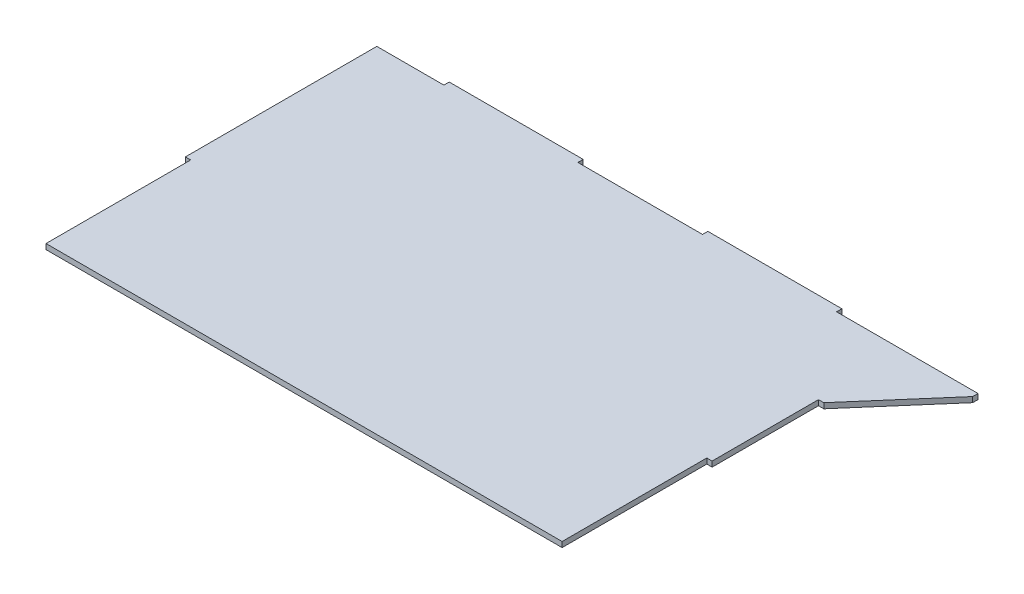
SolidWorks part; units mm, degrees
material "6061-T6 (SS)"
ref_plane "X-Y Datum" through (0, 0, 0) normal (0, 0, 1) x (1, 0, 0)
ref_plane "X-Z Datum" through (0, 0, 0) normal (0, 1, 0) x (1, 0, 0)
ref_plane "Y-Z Datum" through (0, 0, 0) normal (1, 0, 0) x (0, 0, -1)
sketch "Sketch1" plane through (0, 0, 0) normal (0, 0, 1) x (1, 0, 0)
  line L1 (-157.2306, -1.5875) -> (157.2306, -1.5875)
  line L2 (-157.2306, -1.5875) -> (-157.2306, 1.5875)
  line L3 (-157.2306, 1.5875) -> (157.2306, 1.5875)
  line L4 (157.2306, -1.5875) -> (157.2306, 1.5875)
  line L5 (-157.2306, -1.5875) -> (157.2306, 1.5875) construction
  line L6 (-157.2306, 1.5875) -> (157.2306, -1.5875) construction
  point P0 (0, 0)
  dimension "D1" = 314.4612
  dimension "D2" = 3.175
extrude "Boss-Extrude1" add sketch "Sketch1" along normal blind 200.6618
sketch "Sketch3" plane through (0, 0, 0) normal (0, 0, -1) x (-1, 0, 0)
  line L0 (-157.2306, 0) -> (-77.2306, 0) construction
  line L1 (-157.2306, -1.5875) -> (-157.2306, 1.5875) construction
  line L2 (-157.2306, 1.5875) -> (157.2306, 1.5875) construction
  line L3 (-117.2306, -1.5875) -> (-37.2306, -1.5875)
  line L4 (-117.2306, -1.5875) -> (-117.2306, 1.5875)
  line L5 (-117.2306, 1.5875) -> (-37.2306, 1.5875)
  line L6 (-37.2306, -1.5875) -> (-37.2306, 1.5875)
  line L7 (-117.2306, -1.5875) -> (-37.2306, 1.5875) construction
  line L8 (-117.2306, 1.5875) -> (-37.2306, -1.5875) construction
  line L14 (-157.2306, 1.5875) -> (-117.2306, 1.5875)
  line L15 (-157.2306, 1.5875) -> (-157.2306, -1.5875)
  line L16 (-157.2306, -1.5875) -> (-117.2306, -1.5875)
  line L17 (-117.2306, 1.5875) -> (-117.2306, -1.5875)
  line L19 (-37.2306, 1.5875) -> (-37.2306, -1.5875)
  line M3 (-157.2306, -1.5875) -> (157.2306, -1.5875)
  line M5 (157.2306, 1.5875) -> (-157.2306, 1.5875)
  dimension "D1" = 40
  dimension "D2" = 80
sketch "Sketch5" plane through (0, 1.5875, 0) normal (0, 1, 0) x (1, 0, 0)
  line L1 (-157.2306, -200.6618) -> (-154.0556, -200.6618)
  line L3 (-157.2306, -200.6618) -> (-157.2306, -114.3018)
  line L5 (-157.2306, -114.3018) -> (-154.0556, -114.3018)
  line L6 (-154.0556, -200.6618) -> (-154.0556, -114.3018)
  dimension "D1" = 86.36
  dimension "D2" = 3.175
extrude "Cut-Extrude2" cut sketch "Sketch5" against normal blind 3.175 and the other way through all
mirror "Mirror1" about plane through (0, 0, 0) normal (1, 0, 0) of "Cut-Extrude2"
sketch "Sketch6" plane through (0, 1.5875, 0) normal (0, 1, 0) x (1, 0, 0)
  line L6 (-157.2306, -180.3418) -> (-81.0306, -180.3418)
  line L7 (-157.2306, -180.3418) -> (-157.2306, -200.6618)
  line L8 (-157.2306, -200.6618) -> (-81.0306, -200.6618)
  line L9 (-81.0306, -180.3418) -> (-81.0306, -200.6618)
  line L10 (154.0556, -200.6618) -> (-154.0556, -200.6618) construction
  line L11 (-157.2306, -114.3018) -> (-157.2306, 0) construction
  line L13 (154.0556, -200.6618) -> (-81.0306, -200.6618)
  line L14 (154.0556, -200.6618) -> (154.0556, -180.3418)
  line L15 (154.0556, -180.3418) -> (-81.0306, -180.3418)
  line L16 (-81.0306, -200.6618) -> (-81.0306, -180.3418)
  line M18 (-154.0556, -114.3018) -> (-154.0556, -200.6618)
  line M19 (-154.0556, -200.6618) -> (154.0556, -200.6618)
  dimension "D1" = 76.2
  dimension "D2" = 20.32
extrude "Cut-Extrude4" [suppressed] cut sketch "Sketch6" against normal through all contours L9 L6 M18 M19
sketch "Sketch7" [suppressed] plane through (0, 1.5875, 0) normal (0, 1, 0) x (1, 0, 0)
  line L1 (-81.2823, -215.455) -> (155.1963, -215.455)
  line L2 (-81.2823, -215.455) -> (-81.2823, -235.775)
  line L3 (-81.2823, -235.775) -> (155.1963, -235.775)
  line L4 (155.1963, -215.455) -> (155.1963, -235.775)
extrude "Cut-Extrude5" [suppressed] cut sketch "Sketch7" against normal through all
sketch "Sketch8" [suppressed] plane through (0, 1.5875, 0) normal (0, 1, 0) x (1, 0, 0)
  line L0 (155.1963, -235.775) -> (-155.1963, -235.775) construction
  line L1 (157.4823, -215.455) -> (81.2823, -215.455)
  line L2 (157.4823, -215.455) -> (157.4823, -235.775)
  line L3 (157.4823, -235.775) -> (81.2823, -235.775)
  line L4 (81.2823, -215.455) -> (81.2823, -235.775)
  line L5 (157.4823, -117.411) -> (157.4823, -3.175) construction
  dimension "D1" = 20.32
  dimension "D2" = 76.2
extrude "Cut-Extrude6" [suppressed] cut sketch "Sketch8" against normal through all
sketch "Sketch9" [suppressed] plane through (0, 0, 215.455) normal (0, 0, 1) x (1, 0, 0)
  line L4 (155.1963, 1.5875) -> (-155.1963, 1.5875)
  line L5 (-155.1963, 1.5875) -> (-155.1963, -1.5875)
  line L6 (-155.1963, -1.5875) -> (155.1963, -1.5875)
  line L7 (155.1963, -1.5875) -> (155.1963, 1.5875)
  line L8 (155.1963, 1.5875) -> (-155.1963, 1.5875)
  line L9 (-155.1963, 1.5875) -> (-155.1963, -1.5875)
  line L10 (-155.1963, -1.5875) -> (155.1963, -1.5875)
  line L11 (155.1963, -1.5875) -> (155.1963, 1.5875)
  dimension "D1" = 0
extrude "Cut-Extrude7" [suppressed] cut sketch "Sketch9" against normal blind 11.68
extrude "Boss-Extrude2" add sketch "Sketch3" along normal blind 3.175 contours L6 L4 M3 M5
pattern_linear "LPattern2" count 2 spacing 154.43 along (-1, 0, 0) of "Boss-Extrude2"
sketch "Sketch10" plane through (0, -1.5875, 0) normal (0, -1, 0) x (1, 0, 0)
  line L2 (201.6654, 0) -> (201.6654, 3.175)
  line L8 (157.2306, 0) -> (201.6654, 0)
  line L10 (157.2306, 114.3018) -> (157.2306, 0) construction
  line L11 (157.2306, 50.8) -> (157.2306, 0)
  line L12 (157.2306, 50.8) -> (160.4056, 50.8)
  line L13 (160.4056, 50.8) -> (201.6654, 3.175)
  dimension "D1" = 50.8
  dimension "D2" = 44.4348
  dimension "D3" = 3.175
  dimension "D4" = 3.175
extrude "Boss-Extrude3" add sketch "Sketch10" against normal blind 3.175
sketch "Sketch11" [suppressed] plane through (0, 0, 0) normal (0, 0, -1) x (-1, 0, 0)
  line L1 (37.2652, -1.5875) -> (117.2652, -1.5875)
  line L2 (37.2652, -1.5875) -> (37.2652, 1.5875)
  line L3 (37.2652, 1.5875) -> (117.2652, 1.5875)
  line L4 (117.2652, -1.5875) -> (117.2652, 1.5875)
  line L5 (-117.1668, -1.5875) -> (-37.1668, -1.5875)
  line L6 (-117.1668, -1.5875) -> (-117.1668, 1.5875)
  line L7 (-117.1668, 1.5875) -> (-37.1668, 1.5875)
  line L8 (-37.1668, -1.5875) -> (-37.1668, 1.5875)
extrude "Boss-Extrude4" [suppressed] add sketch "Sketch11" along normal blind 3.175
